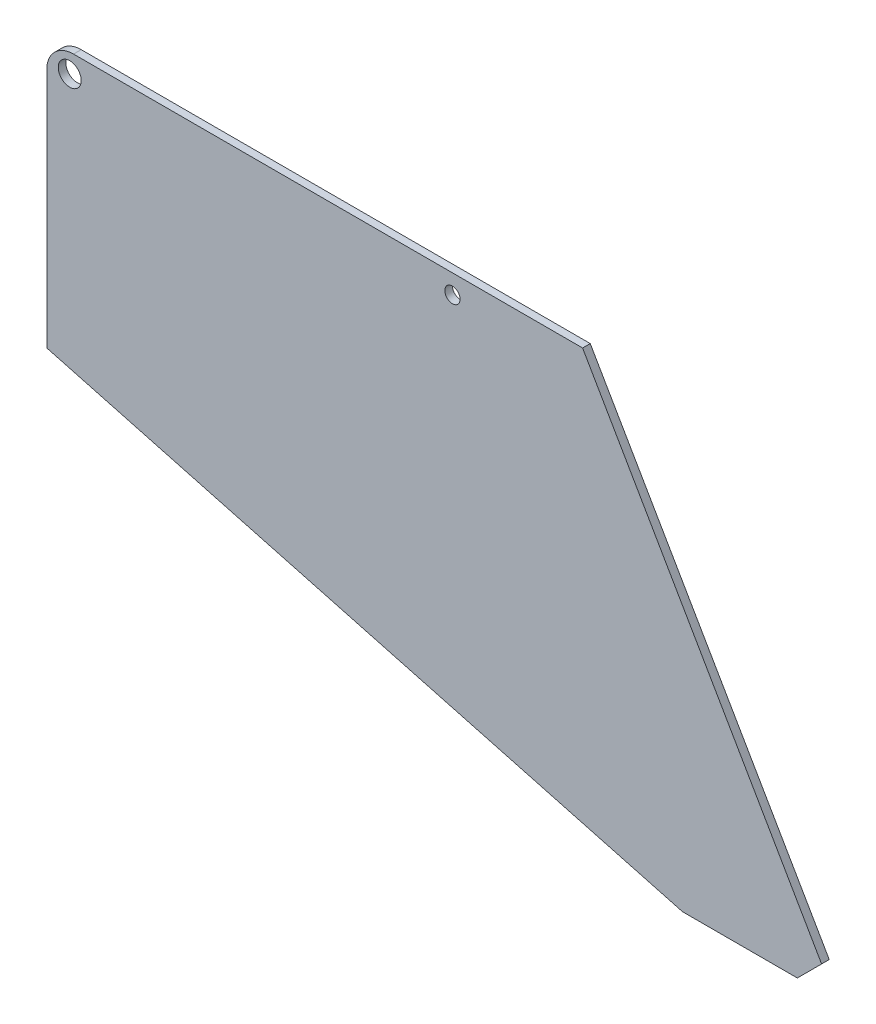
SolidWorks part; units mm, degrees
ref_plane "Front Plane" through (0, 0, 0) normal (0, 0, 1) x (1, 0, 0)
ref_plane "Top Plane" through (0, 0, 0) normal (0, 1, 0) x (1, 0, 0)
ref_plane "Right Plane" through (0, 0, 0) normal (1, 0, 0) x (0, 0, -1)
sketch "Sketch1" plane through (0, 0, 0) normal (0, 0, 1) x (1, 0, 0)
  line L4 (-350, -175) -> (480.5608, -397.5481)
  line L5 (350, 175) -> (-350, 175)
  line L6 (350, 175) -> (350, -175)
  line L7 (350, -175) -> (-350, -175)
  line L8 (-350, 175) -> (-350, -175)
  line L9 (350, 175) -> (-350, -175) construction
  line L10 (350, -175) -> (-350, 175) construction
  line L11 (680.5608, -397.5481) -> (350, 175)
  line L12 (480.5608, -397.5481) -> (680.5608, -397.5481)
  point P0 (0, 0)
  dimension "D1" = 350
  dimension "D2" = 700
  dimension "D3" = 15
  dimension "D4" = 30
  dimension "D5" = 200
extrude "Boss-Extrude2" add sketch "Sketch1" along normal mid plane 10 contours L5 L8 L7 L6 | L4 L11 L6 L7
sketch "Sketch2" plane through (0, 0, 5) normal (0, 0, 1) x (1, 0, 0)
  line L0 (350, 175) -> (-350, 175) construction
  line L1 (-350, 175) -> (-350, -175) construction
  circle A0 centre (-320, 150) radius 15
  circle A1 centre (180, 150) radius 10
  dimension "D1" = 30
  dimension "D4" = 20
  dimension "D2" = 25
  dimension "D3" = 30
  dimension "D5" = 500
extrude "Cut-Extrude1" cut sketch "Sketch2" against normal blind 10
fillet "Fillet1" radius 35 1 edges at (-350, 175, 0)
chamfer "Chamfer1" distance 50 angle 45 1 edges at (680.5608, -397.5481, 0)
